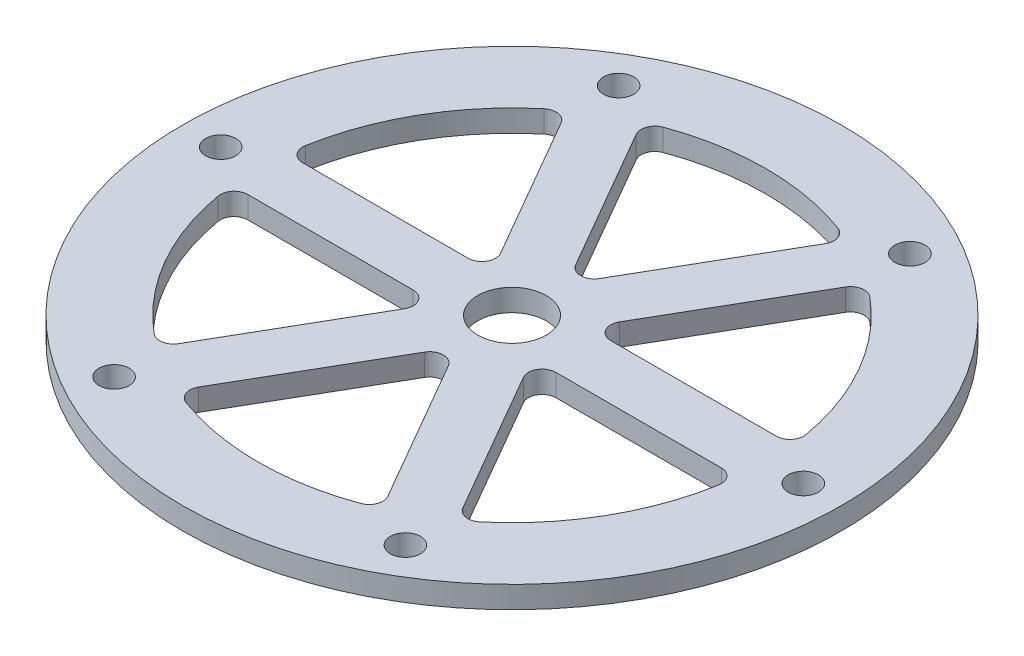
SolidWorks part; units mm, degrees
ref_plane "Front Plane" through (0, 0, 0) normal (0, 0, 1) x (1, 0, 0)
ref_plane "Top Plane" through (0, 0, 0) normal (0, 1, 0) x (1, 0, 0)
ref_plane "Right Plane" through (0, 0, 0) normal (1, 0, 0) x (0, 0, -1)
sketch "Sketch1" plane through (0, 0, 0) normal (0, 1, 0) x (1, 0, 0)
  line L0 (0, 0) -> (-18.5, 0) construction
  line L1 (0, 2) -> (-18.5, 2)
  line L2 (0, -2) -> (-18.5, -2)
  line L3 (-1.7321, -1) -> (-10.9821, 15.0215)
  line L4 (1.7321, 1) -> (-7.5179, 17.0215)
  line L5 (-1.7321, 1) -> (7.5179, 17.0215)
  line L6 (1.7321, -1) -> (10.9821, 15.0215)
  line L7 (0, 2) -> (18.5, 2)
  line L8 (0, -2) -> (18.5, -2)
  line L9 (1.7321, 1) -> (10.9821, -15.0215)
  line L10 (-1.7321, -1) -> (7.5179, -17.0215)
  line L11 (1.7321, -1) -> (-7.5179, -17.0215)
  line L12 (-1.7321, 1) -> (-10.9821, -15.0215)
  circle A0 centre (0, 0) radius 21.2135 construction
  circle A1 centre (-21.2135, 0) radius 1.1
  circle A2 centre (-10.6067, 18.3714) radius 1.1
  circle A3 centre (10.6068, 18.3714) radius 1.1
  circle A4 centre (21.2135, 0) radius 1.1
  circle A5 centre (10.6067, -18.3714) radius 1.1
  circle A6 centre (-10.6068, -18.3714) radius 1.1
  circle A9 centre (0, 0) radius 24
  circle A10 centre (0, 0) radius 18.5
  point P15 (0, 0)
  point P49 (0, 0)
  point P51 (0.001, 0)
  dimension "D1" = 6
  dimension "D2" = 2
  dimension "D3" = 2
extrude "Boss-Extrude1" add sketch "Sketch1" along normal blind 1.6
fillet "Fillet1" radius 1 18 edges at (-3.4641, 0.8, 2) (0, 0.8, 4) (3.4641, 0.8, 2) (3.4641, 0.8, -2) (0, 0.8, -4) (-3.4641, 0.8, -2) (-18.3916, 0.8, 2) (-18.3916, 0.8, -2) (-10.9278, 0.8, 14.9276) (-7.4637, 0.8, 16.9276) (7.4637, 0.8, 16.9276) (10.9278, 0.8, 14.9276) (18.3916, 0.8, 2) (18.3916, 0.8, -2) (10.9278, 0.8, -14.9276) (-7.4637, 0.8, -16.9276) (7.4637, 0.8, -16.9276) (-10.9278, 0.8, -14.9276)
sketch "Sketch2" plane through (0, 1.6, 0) normal (0, 1, 0) x (1, 0, 0)
  circle A0 centre (0, 0) radius 2.5
extrude "Cut-Extrude1" cut sketch "Sketch2" against normal through all
